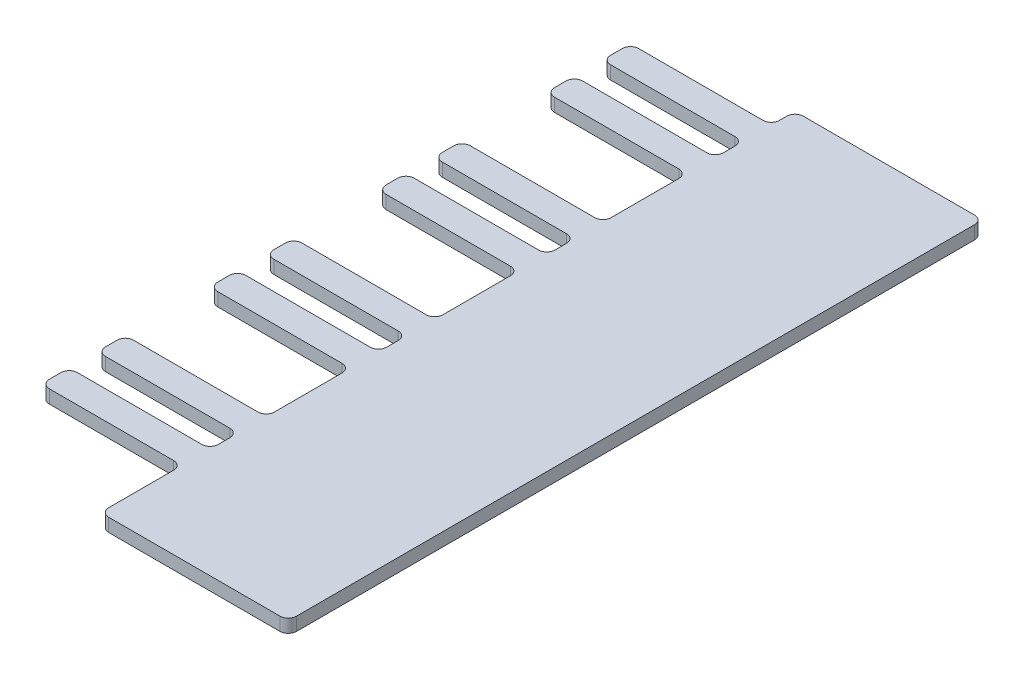
SolidWorks part; units mm, degrees
ref_plane "Front Plane" through (0, 0, 0) normal (0, 0, 1) x (1, 0, 0)
ref_plane "Top Plane" through (0, 0, 0) normal (0, 1, 0) x (1, 0, 0)
ref_plane "Right Plane" through (0, 0, 0) normal (1, 0, 0) x (0, 0, -1)
sketch "Sketch1" plane through (0, 0, 0) normal (0, 1, 0) x (1, 0, 0)
  line L0 (-0.75, 7.382) -> (-12, 7.382)
  line L2 (0, 6.632) -> (0, 0.75)
  line L5 (-12.75, 8.652) -> (0, 8.652) construction
  line L7 (-12.75, 8.132) -> (-12.75, 9.172)
  line L8 (-12, 9.922) -> (-0.75, 9.922)
  line L12 (0, 11.712) -> (0, 10.672)
  line L17 (-0.75, 12.462) -> (-12, 12.462)
  line L22 (-12.75, 13.212) -> (-12.75, 14.252)
  line L27 (-12, 15.002) -> (-0.75, 15.002)
  line L56 (16.25, 0) -> (0.75, 0)
  line L84 (0, 16.792) -> (0, 10.91) [skipped]
  line L85 (-0.75, 17.542) -> (-12, 17.542) [skipped]
  line L86 (-12.75, 18.292) -> (-12.75, 19.332) [skipped]
  line L87 (-12, 20.082) -> (-0.75, 20.082) [skipped]
  line L88 (0, 21.872) -> (0, 15.99) [skipped]
  line L89 (-0.75, 22.622) -> (-12, 22.622) [skipped]
  line L90 (-12.75, 23.372) -> (-12.75, 24.412) [skipped]
  line L91 (-12, 25.162) -> (-0.75, 25.162) [skipped]
  line L92 (0, 26.952) -> (0, 21.07) [skipped]
  line L93 (-0.75, 27.702) -> (-12, 27.702) [skipped]
  line L94 (-12.75, 28.452) -> (-12.75, 29.492) [skipped]
  line L95 (-12, 30.242) -> (-0.75, 30.242) [skipped]
  line L96 (0, 32.032) -> (0, 26.15) [skipped]
  line L97 (-0.75, 32.782) -> (-12, 32.782) [skipped]
  line L98 (-12.75, 33.532) -> (-12.75, 34.572) [skipped]
  line L99 (-12, 35.322) -> (-0.75, 35.322) [skipped]
  line L100 (0, 37.112) -> (0, 31.23) [skipped]
  line L101 (-0.75, 37.862) -> (-12, 37.862) [skipped]
  line L102 (-12.75, 38.612) -> (-12.75, 39.652) [skipped]
  line L103 (-12, 40.402) -> (-0.75, 40.402) [skipped]
  line L104 (0, 42.192) -> (0, 36.31) [skipped]
  line L105 (-0.75, 42.942) -> (-12, 42.942) [skipped]
  line L106 (-12.75, 43.692) -> (-12.75, 44.732) [skipped]
  line L107 (-12, 45.482) -> (-0.75, 45.482) [skipped]
  line L108 (0, 47.272) -> (0, 41.39) [skipped]
  line L109 (-0.75, 48.022) -> (-12, 48.022) [skipped]
  line L110 (-12.75, 48.772) -> (-12.75, 49.812) [skipped]
  line L111 (-12, 50.562) -> (-0.75, 50.562) [skipped]
  line L112 (0, 52.352) -> (0, 46.47) [skipped]
  line L113 (-0.75, 53.102) -> (-12, 53.102) [skipped]
  line L114 (-12.75, 53.852) -> (-12.75, 54.892) [skipped]
  line L115 (-12, 55.642) -> (-0.75, 55.642) [skipped]
  line L116 (-0.75, 22.622) -> (-12, 22.622)
  line L117 (-12.75, 23.372) -> (-12.75, 24.412)
  line L118 (-12, 25.162) -> (-0.75, 25.162)
  line L119 (0, 26.952) -> (0, 25.912)
  line L120 (-0.75, 27.702) -> (-12, 27.702)
  line L121 (-12.75, 28.452) -> (-12.75, 29.492)
  line L122 (-12, 30.242) -> (-0.75, 30.242)
  line L123 (-0.75, 37.862) -> (-12, 37.862)
  line L124 (-12.75, 38.612) -> (-12.75, 39.652)
  line L125 (-12, 40.402) -> (-0.75, 40.402)
  line L126 (0, 42.192) -> (0, 41.152)
  line L127 (-0.75, 42.942) -> (-12, 42.942)
  line L128 (-12.75, 43.692) -> (-12.75, 44.732)
  line L129 (-12, 45.482) -> (-0.75, 45.482)
  line L130 (-0.75, 53.102) -> (-12, 53.102)
  line L131 (-12.75, 53.852) -> (-12.75, 54.892)
  line L132 (-12, 55.642) -> (-0.75, 55.642)
  line L133 (0, 57.432) -> (0, 56.392)
  line L134 (-0.75, 58.182) -> (-12, 58.182)
  line L135 (-12.75, 58.932) -> (-12.75, 59.972)
  line L136 (-12, 60.722) -> (-0.75, 60.722)
  line L137 (0, 21.872) -> (0, 15.752)
  line L138 (0, 30.992) -> (0, 37.112)
  line L139 (0, 46.232) -> (0, 52.352)
  line L140 (0, 61.472) -> (0, 62.122)
  line L141 (0.75, 62.872) -> (16.25, 62.872)
  line L142 (17, 62.122) -> (17, 0.75)
  arc A0 (-0.75, 9.922) -> (0, 10.672) centre (-0.75, 10.672) ccw
  arc A1 (-12.75, 9.172) -> (-12, 9.922) centre (-12, 9.172) cw
  arc A2 (-12, 7.382) -> (-12.75, 8.132) centre (-12, 8.132) cw
  arc A3 (0, 0.75) -> (0.75, 0) centre (0.75, 0.75) ccw
  arc A4 (-0.75, 7.382) -> (0, 6.632) centre (-0.75, 6.632) cw
  arc A5 (17, 0.75) -> (16.25, 0) centre (16.25, 0.75) cw
  arc A6 (-0.75, 12.462) -> (0, 11.712) centre (-0.75, 11.712) cw
  arc A7 (-12, 12.462) -> (-12.75, 13.212) centre (-12, 13.212) cw
  arc A8 (-12.75, 14.252) -> (-12, 15.002) centre (-12, 14.252) cw
  arc A9 (-0.75, 15.002) -> (0, 15.752) centre (-0.75, 15.752) ccw
  arc A44 (-0.75, 17.542) -> (0, 16.792) centre (-0.75, 16.792) cw [skipped]
  arc A45 (-12, 17.542) -> (-12.75, 18.292) centre (-12, 18.292) cw [skipped]
  arc A46 (-12.75, 19.332) -> (-12, 20.082) centre (-12, 19.332) cw [skipped]
  arc A47 (-0.75, 20.082) -> (0, 20.832) centre (-0.75, 20.832) ccw [skipped]
  arc A48 (-0.75, 22.622) -> (0, 21.872) centre (-0.75, 21.872) cw [skipped]
  arc A49 (-12, 22.622) -> (-12.75, 23.372) centre (-12, 23.372) cw [skipped]
  arc A50 (-12.75, 24.412) -> (-12, 25.162) centre (-12, 24.412) cw [skipped]
  arc A51 (-0.75, 25.162) -> (0, 25.912) centre (-0.75, 25.912) ccw [skipped]
  arc A52 (-0.75, 27.702) -> (0, 26.952) centre (-0.75, 26.952) cw [skipped]
  arc A53 (-12, 27.702) -> (-12.75, 28.452) centre (-12, 28.452) cw [skipped]
  arc A54 (-12.75, 29.492) -> (-12, 30.242) centre (-12, 29.492) cw [skipped]
  arc A55 (-0.75, 30.242) -> (0, 30.992) centre (-0.75, 30.992) ccw [skipped]
  arc A56 (-0.75, 32.782) -> (0, 32.032) centre (-0.75, 32.032) cw [skipped]
  arc A57 (-12, 32.782) -> (-12.75, 33.532) centre (-12, 33.532) cw [skipped]
  arc A58 (-12.75, 34.572) -> (-12, 35.322) centre (-12, 34.572) cw [skipped]
  arc A59 (-0.75, 35.322) -> (0, 36.072) centre (-0.75, 36.072) ccw [skipped]
  arc A60 (-0.75, 37.862) -> (0, 37.112) centre (-0.75, 37.112) cw [skipped]
  arc A61 (-12, 37.862) -> (-12.75, 38.612) centre (-12, 38.612) cw [skipped]
  arc A62 (-12.75, 39.652) -> (-12, 40.402) centre (-12, 39.652) cw [skipped]
  arc A63 (-0.75, 40.402) -> (0, 41.152) centre (-0.75, 41.152) ccw [skipped]
  arc A64 (-0.75, 42.942) -> (0, 42.192) centre (-0.75, 42.192) cw [skipped]
  arc A65 (-12, 42.942) -> (-12.75, 43.692) centre (-12, 43.692) cw [skipped]
  arc A66 (-12.75, 44.732) -> (-12, 45.482) centre (-12, 44.732) cw [skipped]
  arc A67 (-0.75, 45.482) -> (0, 46.232) centre (-0.75, 46.232) ccw [skipped]
  arc A68 (-0.75, 48.022) -> (0, 47.272) centre (-0.75, 47.272) cw [skipped]
  arc A69 (-12, 48.022) -> (-12.75, 48.772) centre (-12, 48.772) cw [skipped]
  arc A70 (-12.75, 49.812) -> (-12, 50.562) centre (-12, 49.812) cw [skipped]
  arc A71 (-0.75, 50.562) -> (0, 51.312) centre (-0.75, 51.312) ccw [skipped]
  arc A72 (-0.75, 53.102) -> (0, 52.352) centre (-0.75, 52.352) cw [skipped]
  arc A73 (-12, 53.102) -> (-12.75, 53.852) centre (-12, 53.852) cw [skipped]
  arc A74 (-12.75, 54.892) -> (-12, 55.642) centre (-12, 54.892) cw [skipped]
  arc A75 (-0.75, 55.642) -> (0, 56.392) centre (-0.75, 56.392) ccw [skipped]
  arc A76 (-0.75, 25.162) -> (0, 25.912) centre (-0.75, 25.912) ccw
  arc A77 (-12.75, 24.412) -> (-12, 25.162) centre (-12, 24.412) cw
  arc A78 (-12, 22.622) -> (-12.75, 23.372) centre (-12, 23.372) cw
  arc A79 (-0.75, 22.622) -> (0, 21.872) centre (-0.75, 21.872) cw
  arc A80 (-0.75, 27.702) -> (0, 26.952) centre (-0.75, 26.952) cw
  arc A81 (-12, 27.702) -> (-12.75, 28.452) centre (-12, 28.452) cw
  arc A82 (-12.75, 29.492) -> (-12, 30.242) centre (-12, 29.492) cw
  arc A83 (-0.75, 30.242) -> (0, 30.992) centre (-0.75, 30.992) ccw
  arc A84 (-0.75, 40.402) -> (0, 41.152) centre (-0.75, 41.152) ccw
  arc A85 (-12.75, 39.652) -> (-12, 40.402) centre (-12, 39.652) cw
  arc A86 (-12, 37.862) -> (-12.75, 38.612) centre (-12, 38.612) cw
  arc A87 (-0.75, 37.862) -> (0, 37.112) centre (-0.75, 37.112) cw
  arc A88 (-0.75, 42.942) -> (0, 42.192) centre (-0.75, 42.192) cw
  arc A89 (-12, 42.942) -> (-12.75, 43.692) centre (-12, 43.692) cw
  arc A90 (-12.75, 44.732) -> (-12, 45.482) centre (-12, 44.732) cw
  arc A91 (-0.75, 45.482) -> (0, 46.232) centre (-0.75, 46.232) ccw
  arc A92 (-0.75, 55.642) -> (0, 56.392) centre (-0.75, 56.392) ccw
  arc A93 (-12.75, 54.892) -> (-12, 55.642) centre (-12, 54.892) cw
  arc A94 (-12, 53.102) -> (-12.75, 53.852) centre (-12, 53.852) cw
  arc A95 (-0.75, 53.102) -> (0, 52.352) centre (-0.75, 52.352) cw
  arc A96 (-0.75, 58.182) -> (0, 57.432) centre (-0.75, 57.432) cw
  arc A97 (-12, 58.182) -> (-12.75, 58.932) centre (-12, 58.932) cw
  arc A98 (-12.75, 59.972) -> (-12, 60.722) centre (-12, 59.972) cw
  arc A99 (-0.75, 60.722) -> (0, 61.472) centre (-0.75, 61.472) ccw
  arc A100 (0, 62.122) -> (0.75, 62.872) centre (0.75, 62.122) cw
  arc A101 (16.25, 62.872) -> (17, 62.122) centre (16.25, 62.122) cw
  point P0 (0, 0)
  point P48 (-12.75, 9.922)
  point P69 (-12.75, 7.382)
  point P78 (0, 0)
  point P81 (0, 7.382)
  point P123 (-6.375, 60.722)
  dimension "D6" = 0.75
  dimension "D7" = 0.75
  dimension "D8" = 4
  dimension "D9" = 10.16
  dimension "D11" = 0.75
  dimension "D1" = 2.54
  dimension "D2" = 12
  dimension "D3" = 10
  dimension "D4" = 7.382
  dimension "D5" = 17
  dimension "D10" = 5.08
  dimension "D12" = 2.15
extrude "Boss-Extrude1" add sketch "Sketch1" along normal blind 1.2
